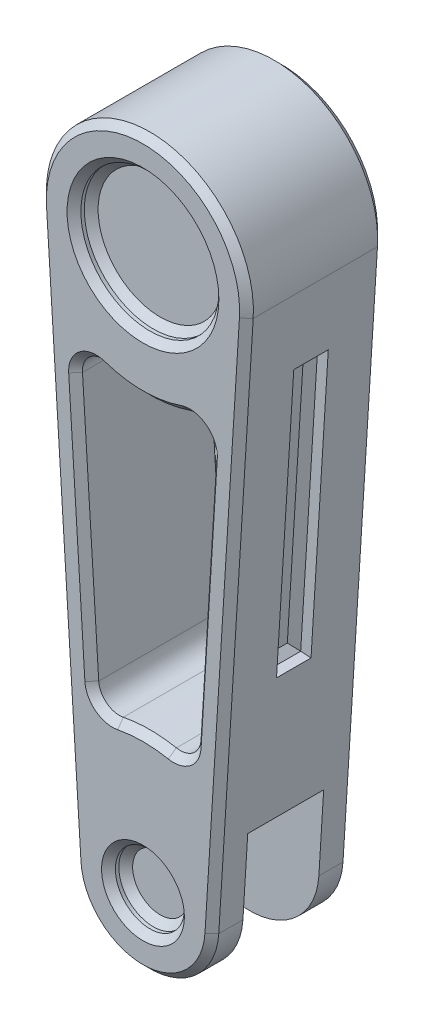
SolidWorks part; units mm, degrees
ref_plane "Front Plane" through (0, 0, 0) normal (0, 0, 1) x (1, 0, 0)
ref_plane "Top Plane" through (0, 0, 0) normal (0, 1, 0) x (1, 0, 0)
ref_plane "Right Plane" through (0, 0, 0) normal (1, 0, 0) x (0, 0, -1)
sketch "Sketch1" plane through (0, 0, 0) normal (0, 0, 1) x (1, 0, 0)
  line L0 (0, 0) -> (0, -160) construction
  line L1 (-29.9413, -1.875) -> (-19.9609, -161.25)
  line L2 (29.9413, -1.875) -> (19.9609, -161.25)
  arc A0 (29.9413, -1.875) -> (-29.9413, -1.875) centre (0, 0) ccw
  arc A1 (-19.9609, -161.25) -> (19.9609, -161.25) centre (0, -160) ccw
  dimension "D1" = 60
  dimension "D3" = 40
  dimension "D2" = 160
extrude "Boss-Extrude1" add sketch "Sketch1" along normal mid plane 40
sketch "Sketch2" plane through (0, 0, -20) normal (0, 0, -1) x (-1, 0, 0)
  circle A0 centre (0, 0) radius 26
  dimension "D1" = 52
extrude "Cut-Extrude1" cut sketch "Sketch2" against normal blind 5
sketch "Sketch3" plane through (0, 0, 0) normal (0, 0, 1) x (1, 0, 0)
  circle A0 centre (0, -160) radius 30
  dimension "D1" = 60
extrude "Cut-Extrude2" cut sketch "Sketch3" against normal mid plane 22
sketch "Sketch4" plane through (0, 0, -20) normal (0, 0, -1) x (-1, 0, 0)
  line L4 (-21.957, -1.375) -> (-11.9765, -160.75)
  line L5 (11.9765, -160.75) -> (21.957, -1.375)
  line L6 (-20.176, -29.8149) -> (-14.3614, -122.667)
  line L7 (14.3614, -122.667) -> (20.176, -29.8149)
  line L8 (-21.3584, -138.933) -> (-19.9609, -161.25)
  line L9 (19.9609, -161.25) -> (21.3584, -138.933)
  line L10 (-21.3584, -138.933) -> (-19.9609, -161.25)
  line L11 (19.9609, -161.25) -> (21.3584, -138.933)
  arc A0 (19.2297, -124.9256) -> (-19.2297, -124.9256) centre (0, -160) ccw construction
  arc A1 (14.3614, -122.667) -> (-14.3614, -122.667) centre (0, -160) ccw
  circle A2 centre (0, 0) radius 36
  arc A3 (-20.176, -29.8149) -> (20.176, -29.8149) centre (0, 0) ccw
  arc A4 (21.957, -1.375) -> (-21.957, -1.375) centre (0, 0) ccw
  arc A5 (-11.9765, -160.75) -> (11.9765, -160.75) centre (0, -160) ccw
  arc A8 (21.3584, -138.933) -> (-21.3584, -138.933) centre (0, -160) ccw
  arc A9 (-19.9609, -161.25) -> (19.9609, -161.25) centre (0, -160) ccw
  arc A10 (14.4223, -133.6942) -> (-14.4223, -133.6942) centre (0, -160) ccw construction
  arc A11 (-19.9609, -161.25) -> (19.9609, -161.25) centre (0, -160) ccw
  dimension "D1" = 8
  dimension "D2" = 0
  dimension "D3" = 10
  dimension "D4" = 10
extrude "Cut-Extrude3" cut sketch "Sketch4" against normal through all contours A3 L6 A1 L7
fillet "Fillet1" radius 6 4 edges at (14.3614, -122.667, 0) (-14.3614, -122.667, 0) (20.176, -29.8149, 0) (-20.176, -29.8149, 0)
chamfer "Chamfer1" distance 2 angle 45 24 edges at (12.5053, -119.6065, 20) (17.1785, -77.6821, 20) (17.1848, -34.9897, 20) (0, -36, 20) (-17.1848, -34.9897, 20) (-17.1785, -77.6821, 20) (-12.5053, -119.6065, 20) (0, -120, 20) (24.9511, -81.5625, 20) (0, -180, 20) (-24.9511, -81.5625, 20) (0, 30, 20) (24.9511, -81.5625, -20) (0, 30, -20) (0, -180, -20) (-24.9511, -81.5625, -20) (17.1785, -77.6821, -20) (12.5053, -119.6065, -20) (17.1848, -34.9897, -20) (0, -120, -20) (0, -36, -20) (-12.5053, -119.6065, -20) (-17.1848, -34.9897, -20) (-17.1785, -77.6821, -20)
sketch "Sketch6" plane through (29.9413, -1.875, 0) normal (0.998, -0.0625, 0) x (0, 0, -1)
  line L0 (0, 0) -> (0, -100) construction
  line L1 (-5, -20) -> (5, -20)
  line L2 (-5, -20) -> (-5, -100)
  line L3 (-5, -100) -> (5, -100)
  line L4 (5, -20) -> (5, -100)
  line L5 (-18, 0) -> (18, 0) construction
  dimension "D1" = 20
  dimension "D2" = 80
  dimension "D3" = 10
extrude "Cut-Extrude4" cut sketch "Sketch6" against normal blind 5
chamfer "Chamfer2" distance 2 angle 45 4 edges at (23.7011, -21.5234, 0) (21.2011, -61.4452, -5) (18.7011, -101.367, 0) (21.2011, -61.4452, 5)
sketch "Sketch7" plane through (0, 0, 20) normal (0, 0, 1) x (1, 0, 0)
  circle A0 centre (0, -160) radius 10
  arc A1 (-19.9609, -161.25) -> (19.9609, -161.25) centre (0, -160) ccw construction
  circle A2 centre (0, 0) radius 20
  arc A3 (29.9413, -1.875) -> (-29.9413, -1.875) centre (0, 0) ccw construction
  dimension "D1" = 10
  dimension "D2" = 10
extrude "Cut-Extrude5" cut sketch "Sketch7" against normal blind 5
chamfer "Chamfer3" distance 2 angle 45 4 edges at (10, -160, 20) (10, -160, 15) (20, 0, 15) (20, 0, 20)
sketch "Sketch8" plane through (0, 0, 0) normal (0, 0, 1) x (1, 0, 0)
  line L0 (0, 30) -> (0, -180) construction
  arc A0 (29.9413, -1.875) -> (-29.9413, -1.875) centre (0, 0) ccw construction
  arc A1 (-19.9609, -161.25) -> (19.9609, -161.25) centre (0, -160) ccw construction
  point P8 (0, -75)
